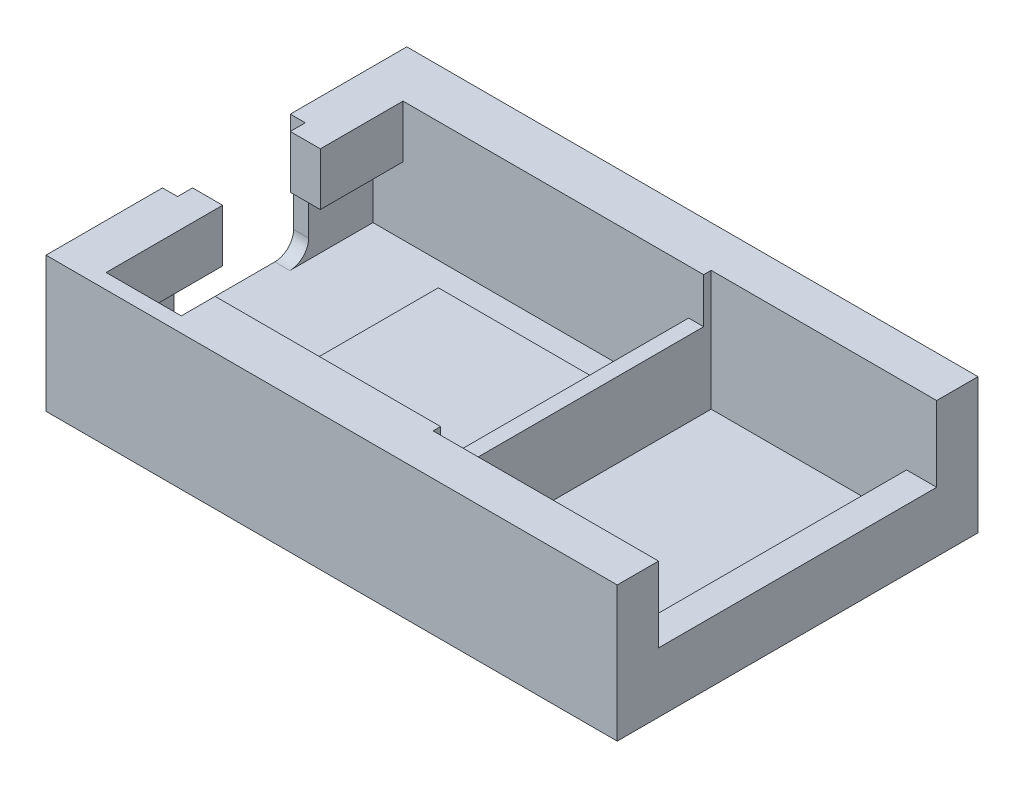
SolidWorks part; units mm, degrees
ref_plane "Front Plane" through (0, 0, 0) normal (0, 0, 1) x (1, 0, 0)
ref_plane "Top Plane" through (0, 0, 0) normal (0, 1, 0) x (1, 0, 0)
ref_plane "Right Plane" through (0, 0, 0) normal (1, 0, 0) x (0, 0, -1)
sketch "Sketch1" plane through (0, 0, 0) normal (0, 1, 0) x (1, 0, 0)
  line L1 (0, 0) -> (40, 0)
  line L2 (0, 0) -> (0, 24)
  line L3 (0, 24) -> (40, 24)
  line L4 (40, 0) -> (40, 24)
  dimension "D1" = 24
  dimension "D2" = 40
extrude "Boss-Extrude1" add sketch "Sketch1" along normal blind 1
sketch "Sketch2" plane through (0, 1, 0) normal (0, 1, 0) x (1, 0, 0)
  line L1 (0, 24) -> (40, 24)
  line L2 (0, 24) -> (0, 0)
  line L3 (0, 0) -> (40, 0)
  line L4 (40, 24) -> (40, 0)
  line L5 (1, 20.75) -> (22, 20.75)
  line L6 (1, 20.75) -> (1, 3.25)
  line L7 (1, 3.25) -> (22, 3.25)
  line L8 (22, 20.75) -> (22, 3.25)
  line L9 (23, 21.25) -> (36, 21.25)
  line L10 (23, 21.25) -> (23, 2.75)
  line L11 (23, 2.75) -> (36, 2.75)
  line L12 (36, 21.25) -> (36, 2.75)
  dimension "D1" = 17.5
  dimension "D2" = 21
  dimension "D3" = 3.25
  dimension "D4" = 1
  dimension "D5" = 18.5
  dimension "D6" = 13
  dimension "D7" = 1
  dimension "D8" = 2.75
extrude "Boss-Extrude3" add sketch "Sketch2" along normal blind 8
sketch "Sketch3" plane through (0, 9, 0) normal (0, 1, 0) x (1, 0, 0)
  line L0 (22, 20.75) -> (23, 20.75)
  line L1 (23, 21.25) -> (23, 2.75) construction
  line L2 (22, 20.75) -> (22, 3.25)
  line L3 (22, 3.25) -> (23, 3.25)
  line L4 (23, 21.25) -> (23, 2.75) construction
  line L5 (23, 3.25) -> (23, 20.75)
extrude "Cut-Extrude2" cut sketch "Sketch3" against normal blind 3
sketch "Sketch4" plane through (0, 1, 0) normal (0, 1, 0) x (1, 0, 0)
  line L0 (22, 20.75) -> (22, 3.25) construction
  line L1 (8.14, 17.96) -> (18.38, 17.96)
  line L2 (8.14, 17.96) -> (8.14, 6.04)
  line L3 (8.14, 6.04) -> (18.38, 6.04)
  line L4 (18.38, 17.96) -> (18.38, 6.04)
  line L5 (22, 20.75) -> (1, 20.75) construction
  line L6 (1, 3.25) -> (22, 3.25) construction
  line L7 (1, 20.75) -> (1, 3.25) construction
  dimension "D1" = 3.62
  dimension "D2" = 2.79
  dimension "D3" = 2.79
  dimension "D4" = 7.14
extrude "Boss-Extrude4" add sketch "Sketch4" along normal blind 1.21
sketch "Sketch5" plane through (1, 0, 0) normal (1, 0, 0) x (0, 0, -1)
  line L0 (7.53, 2.25) -> (7.53, 2.96)
  line L1 (8.78, 1) -> (15.22, 1)
  line L3 (16.47, 2.96) -> (16.47, 2.25)
  line L4 (20.75, 1) -> (3.25, 1) construction
  line L5 (3.25, 9) -> (3.25, 1) construction
  line L6 (7.53, 2.96) -> (7.53, 9)
  line L7 (20.75, 9) -> (3.25, 9) construction
  line L8 (7.53, 9) -> (16.47, 9)
  line L9 (16.47, 9) -> (16.47, 2.96)
  line L10 (20.75, 9) -> (20.75, 1) construction
  arc A0 (7.53, 2.25) -> (8.78, 1) centre (8.78, 2.25) ccw
  arc A3 (15.22, 1) -> (16.47, 2.25) centre (15.22, 2.25) ccw
  dimension "D7" = 1.25
  dimension "D1" = 1.25
  dimension "D2" = 0.71
  dimension "D3" = 6.44
  dimension "D4" = 4.28
  dimension "D9" = 0.71
  dimension "D10" = 4.28
extrude "Cut-Extrude3" cut sketch "Sketch5" against normal blind 2
sketch "Sketch8" plane through (0, 9, 0) normal (0, 1, 0) x (1, 0, 0)
  line L0 (36, 21.25) -> (40, 21.25)
  line L1 (40, 0) -> (40, 24) construction
  line L2 (36, 2.75) -> (40, 2.75)
  line L3 (40, 2.75) -> (40, 21.25)
  line L4 (36, 21.25) -> (36, 2.75)
extrude "Cut-Extrude4" cut sketch "Sketch8" against normal blind 5
sketch "Sketch10" plane through (0, 9, 0) normal (0, 1, 0) x (1, 0, 0)
sketch "Sketch11" plane through (40, 0, 0) normal (1, 0, 0) x (0, 0, -1)
  line L0 (21.25, 9) -> (24, 9) construction
  line L1 (0, 0) -> (24, 0)
  line L2 (0, 0) -> (0, 9)
  line L3 (0, 9) -> (24, 9)
  line L4 (24, 0) -> (24, 9)
  line L5 (24, 9) -> (24, 0) construction
extrude "Cut-Extrude5" cut sketch "Sketch11" against normal blind 2
sketch "Sketch12" plane through (0, 9, 0) normal (0, 1, 0) x (1, 0, 0)
  line L0 (0, 24) -> (0, 16.47) construction
  line L1 (4, 1) -> (8, 1)
  line L2 (4, 1) -> (4, 4)
  line L3 (4, 4) -> (8, 4)
  line L4 (8, 1) -> (8, 4)
  line L5 (0, 0) -> (38, 0) construction
  dimension "D1" = 4
  dimension "D2" = 1
  dimension "D3" = 3
  dimension "D4" = 4
extrude "Cut-Extrude6" cut sketch "Sketch12" against normal blind 3
sketch "Sketch13" plane through (0, 9, 0) normal (0, 1, 0) x (1, 0, 0)
  line L0 (23, 20.75) -> (1, 20.75) construction
  line L2 (1, 16.47) -> (1, 20.75)
  line L3 (1, 20.75) -> (3, 20.75)
  line L5 (3, 20.75) -> (3, 15.25)
  line L8 (1, 3.25) -> (3, 3.25)
  line L10 (1, 3.25) -> (4, 3.25) construction
  line L14 (1, 7.75) -> (0, 7.75)
  line L16 (0, 16.47) -> (1, 16.47)
  line L17 (0, 16.47) -> (0, 16.25)
  line L18 (0, 16.25) -> (1, 16.25)
  line L21 (0, 7.75) -> (0, 7.53)
  line L22 (1, 7.53) -> (1, 3.25)
  line L23 (0, 7.53) -> (1, 7.53)
  line L26 (3, 15.25) -> (1, 15.25)
  line L27 (1, 16.25) -> (1, 15.25)
  line L30 (3, 8.75) -> (1, 8.75)
  line L31 (1, 7.75) -> (1, 8.75)
  line L32 (3, 8.75) -> (3, 3.25)
  dimension "D1" = 0.22
  dimension "D2" = 0.22
  dimension "D3" = 2
  dimension "D4" = 2
  dimension "D5" = 1
  dimension "D6" = 2
  dimension "D7" = 2
  dimension "D8" = 1
extrude "Boss-Extrude5" add sketch "Sketch13" against normal blind 3.5
sketch "Sketch14" plane through (0, 9, 0) normal (0, 1, 0) x (1, 0, 0)
  line L1 (4, 1) -> (3, 1)
  line L2 (4, 1) -> (4, 3.25)
  line L3 (4, 3.25) -> (3, 3.25)
  line L4 (3, 1) -> (3, 3.25)
extrude "Cut-Extrude7" cut sketch "Sketch14" against normal blind 3
